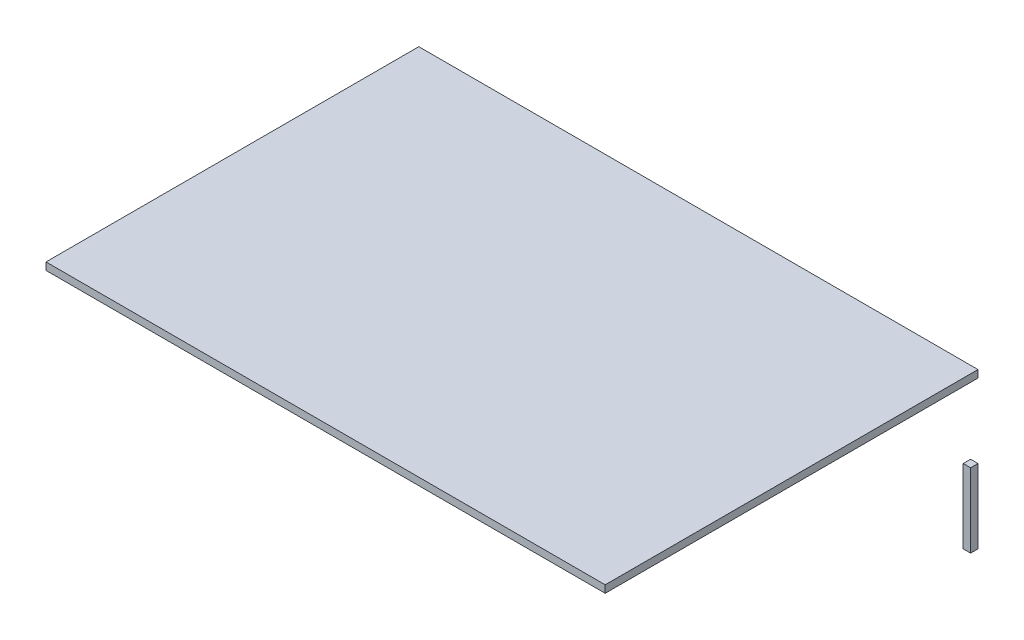
SolidWorks part; units mm, degrees
ref_plane "Front Plane" through (0, 0, 0) normal (0, 0, 1) x (1, 0, 0)
ref_plane "Top Plane" through (0, 0, 0) normal (0, 1, 0) x (1, 0, 0)
ref_plane "Right Plane" through (0, 0, 0) normal (1, 0, 0) x (0, 0, -1)
sketch "Sketch1" plane through (0, 0, 0) normal (0, 1, 0) x (1, 0, 0)
  line L1 (-37.5, -25) -> (37.5, -25)
  line L2 (-37.5, -25) -> (-37.5, 25)
  line L3 (-37.5, 25) -> (37.5, 25)
  line L4 (37.5, -25) -> (37.5, 25)
  line L5 (-37.5, -25) -> (37.5, 25) construction
  line L6 (-37.5, 25) -> (37.5, -25) construction
  point P0 (0, 0)
  dimension "D1" = 50
  dimension "D2" = 75
extrude "Boss-Extrude1" add sketch "Sketch1" along normal blind 10
sketch "Sketch2" plane through (0, 10, 0) normal (0, 1, 0) x (1, 0, 0)
  line L0 (37.5, 0) -> (37.5, 25) construction
  line L1 (37.5, -25) -> (37.5, 25) construction
  line L2 (37.5, 12.5) -> (-37.5, 12.5) construction
  line L3 (-37.5, 25) -> (-37.5, -25) construction
  line L4 (37.5, 19.5) -> (-37.5, 19.5) construction
  text T0 "TEST ONE " font "Century Gothic" height 7
  dimension "D1" = 7
extrude "Boss-Extrude2" add sketch "Sketch2" along normal blind 2
sketch "Sketch3" plane through (0, 10, 0) normal (0, 1, 0) x (1, 0, 0)
  line L0 (-37.5, 0) -> (-31.5, 0) construction
  line L1 (-37.5, 25) -> (-37.5, -25) construction
  line L2 (-31.5, -6) -> (-31.5, 6)
  line L3 (-31.5, 6) -> (-31.5, -6)
  line L4 (-31.5, -6) -> (-30.5, -6)
  line L5 (-30.5, -6) -> (-30.5, 6)
  line L6 (-30.5, 6) -> (-31.5, 6)
  line L7 (-37.5, -0.5) -> (-31.5, -0.5)
  line L8 (-37.5, 0.5) -> (-31.5, 0.5)
  line L9 (-30.5, 0) -> (-27.5, 0)
  line L10 (-29, 0) -> (-29, 1.3474)
  line L11 (-37.5, -0.5) -> (-31.5, -0.5)
  line L12 (-37.5, 0.5) -> (-31.5, 0.5)
  line L13 (-30.5, -6) -> (-31.5, -6)
  line L14 (-31.5, 6) -> (-30.5, 6)
  line L15 (-31.5, -6) -> (-30.5, -6)
  line L16 (-30.5, 6) -> (-31.5, 6)
  line L17 (-37.5, -0.5) -> (-31.5, -0.5)
  line L18 (-37.5, 0.5) -> (-31.5, 0.5)
  line L19 (-37.5, -0.5) -> (-31.5, -0.5)
  line L20 (-37.5, 0.5) -> (-31.5, 0.5)
  line L21 (-30.5, -6) -> (-31.5, -6)
  line L22 (-31.5, 6) -> (-30.5, 6)
  line L23 (-31.5, -6) -> (-30.5, -6)
  line L24 (-30.5, 6) -> (-31.5, 6)
  line L25 (-37.5, -0.5) -> (-31.5, -0.5)
  line L26 (-37.5, 0.5) -> (-31.5, 0.5)
  line L27 (-37.5, -0.5) -> (-31.5, -0.5)
  line L28 (-37.5, 0.5) -> (-31.5, 0.5)
  line L29 (-30.5, -6) -> (-31.5, -6)
  line L30 (-31.5, 6) -> (-30.5, 6)
  line L31 (-31.5, -6) -> (-30.5, -6)
  line L32 (-30.5, 6) -> (-31.5, 6)
  line L33 (-37.5, -0.5) -> (-31.5, -0.5)
  line L34 (-37.5, 0.5) -> (-31.5, 0.5)
  line L35 (-37.5, -0.5) -> (-31.5, -0.5)
  line L36 (-37.5, 0.5) -> (-31.5, 0.5)
  line L37 (-30.5, -6) -> (-31.5, -6)
  line L38 (-31.5, 6) -> (-30.5, 6)
  line L39 (-27.5, 0) -> (-27.5, 6)
  line L40 (-27.5, 6) -> (-26.5, 6)
  line L41 (-26.5, 6) -> (-26.5, -6)
  line L42 (-26.5, -6) -> (-27.5, -6)
  line L43 (-27.5, -6) -> (-27.5, 0)
  line L44 (-26.5, 0) -> (-20.5, 0)
  line L45 (-26.5, -0.5) -> (-20.5, -0.5)
  line L46 (-26.5, 0.5) -> (-20.5, 0.5)
  line L47 (-20.5, 0.5) -> (-20.5, -0.5)
  line L48 (-37.5, 0.5) -> (-37.5, -0.5)
  dimension "D1" = 6
  dimension "D2" = 6
  dimension "D3" = 6
  dimension "D4" = 1
  dimension "D7" = 3
  dimension "D5" = 6
  dimension "D6" = 1
  dimension "D8" = 0.5
  dimension "D9" = 0.5
extrude "Boss-Extrude3" add sketch "Sketch3" along normal blind 2 contours L5 L6 L2 L3 L4 | L48 L0 L2 L8 | L0 L48 L7 L3 | L43 L42 L41 L40 L39 | L47 L46 L41 L44 | L47 L44 L41 L45
sketch "Sketch4" plane through (0, 10, 0) normal (0, 1, 0) x (1, 0, 0)
  line L0 (-20.5, 0) -> (-17.5, 0)
  line L1 (-20.5, 0.5) -> (-20.5, -0.5) construction
  line L2 (-19, 0) -> (-19, 1.3773)
  line L3 (-26.5, -0.5) -> (-20.5, -0.5) construction
  line L4 (-20.5, -0.5) -> (-20.5, 0.5) construction
  line L5 (-20.5, 0.5) -> (-26.5, 0.5) construction
  line L6 (-26.5, 0.5) -> (-26.5, 6) construction
  line L7 (-26.5, 6) -> (-27.5, 6) construction
  line L8 (-27.5, 6) -> (-27.5, -6) construction
  line L9 (-27.5, -6) -> (-26.5, -6) construction
  line L10 (-26.5, -6) -> (-26.5, -0.5) construction
  line L11 (-30.5, -6) -> (-30.5, 6) construction
  line L12 (-30.5, 6) -> (-31.5, 6) construction
  line L13 (-31.5, 6) -> (-31.5, 0.5) construction
  line L14 (-31.5, 0.5) -> (-37.5, 0.5) construction
  line L15 (-37.5, 0.5) -> (-37.5, -0.5) construction
  line L16 (-37.5, -0.5) -> (-31.5, -0.5) construction
  line L17 (-31.5, -0.5) -> (-31.5, -6) construction
  line L18 (-31.5, -6) -> (-30.5, -6) construction
  line L19 (-26.5, -0.5) -> (-20.5, -0.5)
  line L20 (-20.5, -0.5) -> (-20.5, 0.5)
  line L21 (-20.5, 0.5) -> (-26.5, 0.5)
  line L22 (-26.5, 0.5) -> (-26.5, 6)
  line L23 (-26.5, 6) -> (-27.5, 6)
  line L24 (-27.5, 6) -> (-27.5, -6)
  line L25 (-27.5, -6) -> (-26.5, -6)
  line L26 (-26.5, -6) -> (-26.5, -0.5)
  line L27 (-30.5, -6) -> (-30.5, 6)
  line L28 (-30.5, 6) -> (-31.5, 6)
  line L29 (-31.5, 6) -> (-31.5, 0.5)
  line L30 (-31.5, 0.5) -> (-37.5, 0.5)
  line L31 (-37.5, 0.5) -> (-37.5, -0.5)
  line L32 (-37.5, -0.5) -> (-31.5, -0.5)
  line L33 (-31.5, -0.5) -> (-31.5, -6)
  line L34 (-31.5, -6) -> (-30.5, -6)
  line L35 (-6.5, -6) -> (-7.5, -6)
  line L36 (-6.5, -0.5) -> (-6.5, -6)
  line L37 (-0.5, -0.5) -> (-6.5, -0.5)
  line L38 (-0.5, 0.5) -> (-0.5, -0.5)
  line L39 (-6.5, 0.5) -> (-0.5, 0.5)
  line L40 (-6.5, 6) -> (-6.5, 0.5)
  line L41 (-7.5, 6) -> (-6.5, 6)
  line L42 (-7.5, -6) -> (-7.5, 6)
  line L43 (-11.5, -6) -> (-11.5, -0.5)
  line L44 (-10.5, -6) -> (-11.5, -6)
  line L45 (-10.5, 6) -> (-10.5, -6)
  line L46 (-11.5, 6) -> (-10.5, 6)
  line L47 (-11.5, 0.5) -> (-11.5, 6)
  line L48 (-17.5, 0.5) -> (-11.5, 0.5)
  line L49 (-17.5, -0.5) -> (-17.5, 0.5)
  line L50 (-11.5, -0.5) -> (-17.5, -0.5)
  line L51 (-10.5, 6) -> (-6.5, -6)
  line L52 (-7.5, -6) -> (-11.5, 6)
  dimension "D1" = 3
extrude "Boss-Extrude4" add sketch "Sketch4" along normal blind 2 contours L45 L52 L47 L48 L49 L50 L43 L44 | L52 L42 L51 L45 | L52 L45 L46 | L42 L51 L36 L37 L38 L39 L40 L41 | L51 L42 L35
sketch "Sketch5" plane through (0, 0, 25) normal (0, 0, 1) x (1, 0, 0)
  line L4 (-37.5, 0) -> (37.5, 0)
  line L5 (37.5, 0) -> (37.5, 10)
  line L6 (37.5, 10) -> (-37.5, 10)
  line L7 (-37.5, 10) -> (-37.5, 0)
  line L8 (-37.5, 0) -> (37.5, 0)
  line L9 (37.5, 0) -> (37.5, 10)
  line L10 (37.5, 10) -> (-37.5, 10)
  line L11 (-37.5, 10) -> (-37.5, 0)
  dimension "D1" = 0
sketch "Sketch6" plane through (0, 10, 0) normal (0, 1, 0) x (1, 0, 0)
  line L0 (37.7, 25.2) -> (-37.7, 25.2)
  line L1 (-37.7, 25.2) -> (-37.7, 0.3)
  line L2 (-37.7, 0.3) -> (-31.3, 0.3)
  line L3 (-31.3, 0.3) -> (-31.3, 5.8)
  line L4 (-31.3, 5.8) -> (-30.7, 5.8)
  line L5 (-30.7, 5.8) -> (-30.7, -5.8)
  line L6 (-30.7, -5.8) -> (-31.3, -5.8)
  line L7 (-31.3, -5.8) -> (-31.3, -0.3)
  line L8 (-31.3, -0.3) -> (-37.7, -0.3)
  line L9 (-37.7, -0.3) -> (-37.7, -25.2)
  line L10 (-37.7, -25.2) -> (37.7, -25.2)
  line L11 (37.7, -25.2) -> (37.7, 25.2)
  line L12 (-37.5, 25) -> (-37.5, 0.5)
  line L13 (-37.5, 0.5) -> (-31.5, 0.5)
  line L14 (-31.5, 0.5) -> (-31.5, 6)
  line L15 (-31.5, 6) -> (-30.5, 6)
  line L16 (-30.5, 6) -> (-30.5, -6)
  line L17 (-30.5, -6) -> (-31.5, -6)
  line L18 (-31.5, -6) -> (-31.5, -0.5)
  line L19 (-31.5, -0.5) -> (-37.5, -0.5)
  line L20 (-37.5, -0.5) -> (-37.5, -25)
  line L21 (-37.5, -25) -> (37.5, -25)
  line L22 (37.5, -25) -> (37.5, 25)
  line L23 (37.5, 25) -> (-37.5, 25)
  line L24 (-37.5, 25) -> (-37.5, 0.5)
  line L25 (-37.5, 0.5) -> (-31.5, 0.5)
  line L26 (-31.5, 0.5) -> (-31.5, 6)
  line L27 (-31.5, 6) -> (-30.5, 6)
  line L28 (-30.5, 6) -> (-30.5, -6)
  line L29 (-30.5, -6) -> (-31.5, -6)
  line L30 (-31.5, -6) -> (-31.5, -0.5)
  line L31 (-31.5, -0.5) -> (-37.5, -0.5)
  line L32 (-37.5, -0.5) -> (-37.5, -25)
  line L33 (-37.5, -25) -> (37.5, -25)
  line L34 (37.5, -25) -> (37.5, 25)
  line L35 (37.5, 25) -> (-37.5, 25)
  dimension "D1" = 0
  dimension "D2" = 0.2
extrude "Boss-Extrude6" add sketch "Sketch6" against normal through all
sketch "Sketch8" plane through (0, 10, 0) normal (0, 1, 0) x (1, 0, 0)
  line L16 (-37.5, -0.3) -> (-37.5, -25)
  line L17 (-37.5, -25) -> (37.5, -25)
  line L18 (37.5, -25) -> (37.5, 25)
  line L19 (37.5, 25) -> (-37.5, 25)
  line L20 (-37.5, 25) -> (-37.5, 0.3)
  line L21 (-37.7, 0.3) -> (-37.7, -0.3)
  line L22 (-37.5, -0.3) -> (-37.5, 0.3)
  line L32 (-37.5, 0.3) -> (-37.5, 0.5)
  line L33 (-37.5, 0.5) -> (-31.5, 0.5)
  line L34 (-31.5, 0.5) -> (-31.5, 6)
  line L35 (-31.5, 6) -> (-30.5, 6)
  line L36 (-30.5, 6) -> (-30.5, -6)
  line L37 (-30.5, -6) -> (-31.5, -6)
  line L38 (-31.5, -6) -> (-31.5, -0.5)
  line L39 (-31.5, -0.5) -> (-37.5, -0.5)
  line L40 (-37.5, -0.5) -> (-37.5, -0.3)
  line L41 (-37.5, -0.3) -> (-37.7, -0.3)
  line L42 (-37.7, -0.3) -> (-37.7, -25.2)
  line L43 (-37.7, -25.2) -> (37.7, -25.2)
  line L44 (37.7, -25.2) -> (37.7, 25.2)
  line L45 (37.7, 25.2) -> (-37.7, 25.2)
  line L46 (-37.7, 25.2) -> (-37.7, 0.3)
  line L47 (-37.7, 0.3) -> (-37.5, 0.3)
  line L48 (-37.5, 0.3) -> (-37.5, 0.5)
  line L49 (-37.5, 0.5) -> (-31.5, 0.5)
  line L50 (-31.5, 0.5) -> (-31.5, 6)
  line L51 (-31.5, 6) -> (-30.5, 6)
  line L52 (-30.5, 6) -> (-30.5, -6)
  line L53 (-30.5, -6) -> (-31.5, -6)
  line L54 (-31.5, -6) -> (-31.5, -0.5)
  line L55 (-31.5, -0.5) -> (-37.5, -0.5)
  line L56 (-37.5, -0.5) -> (-37.5, -0.3)
  line L57 (-37.5, -0.3) -> (-37.7, -0.3)
  line L58 (-37.7, -0.3) -> (-37.7, -25.2)
  line L59 (-37.7, -25.2) -> (37.7, -25.2)
  line L60 (37.7, -25.2) -> (37.7, 25.2)
  line L61 (37.7, 25.2) -> (-37.7, 25.2)
  line L62 (-37.7, 25.2) -> (-37.7, 0.3)
  line L63 (-37.7, 0.3) -> (-37.5, 0.3)
  dimension "D1" = 0
  dimension "D2" = 0.2
extrude "Cut-Extrude2" cut sketch "Sketch8" against normal through all contours L54 L55 L16 L17 L18 L19 L20 L49 L50 L51 L52 L53
sketch "Sketch9" plane through (-37.7, 0, 0) normal (-1, 0, 0) x (0, 0, 1)
  line L1 (-0.3, 10) -> (0.3, 10)
  line L2 (-0.3, 10) -> (-0.3, 0)
  line L3 (-0.3, 0) -> (0.3, 0)
  line L4 (25.2, 10) -> (0.3, 10)
  line L5 (0.3, 10) -> (0.3, 0)
  line L6 (0.3, 0) -> (25.2, 0)
  line L7 (25.2, 0) -> (25.2, 10)
  line L8 (25.2, 10) -> (0.3, 10)
  line L9 (0.3, 10) -> (0.3, 0)
  line L10 (0.3, 0) -> (25.2, 0)
  line L11 (25.2, 0) -> (25.2, 10)
  line L12 (-0.3, 10) -> (-25.2, 10)
  line L13 (-25.2, 10) -> (-25.2, 0)
  line L14 (-25.2, 0) -> (-0.3, 0)
  line L15 (-0.3, 0) -> (-0.3, 10)
  line L16 (-0.3, 10) -> (-25.2, 10)
  line L17 (-25.2, 10) -> (-25.2, 0)
  line L18 (-25.2, 0) -> (-0.3, 0)
  line L19 (-0.3, 0) -> (-0.3, 10)
  line L20 (0.3, 10) -> (0.3, 0)
  line M9 (25.2, 10) -> (0.3, 10)
  line M10 (0.3, 10) -> (0.3, 0)
  line M11 (0.3, 0) -> (25.2, 0)
  line M12 (25.2, 0) -> (25.2, 10)
  dimension "D1" = 0
  dimension "D2" = 0
extrude "Boss-Extrude8" add sketch "Sketch9" along normal blind 0.2 contours L17 L18 L2 L16 | L2 L3 L1 M10 | M12 M9 M10 M11
sketch "Sketch10" plane through (0, 10, 0) normal (0, 1, 0) x (1, 0, 0)
  line L0 (-37.7, 0.3) -> (-37.7, 25)
  line L1 (-37.5, 25) -> (-37.7, 25)
  line L2 (-37.5, 25) -> (-37.5, -25)
  line L3 (-37.5, -25) -> (-37.7, -25)
  line L4 (-37.7, 0.3) -> (-37.7, -25)
extrude "Cut-Extrude3" cut sketch "Sketch10" against normal through all
ref_plane "Plane1" through (0, 20, 0) normal (0, 1, 0) x (1, 0, 0)
sketch "Sketch11" plane through (0, 20, 0) normal (0, 1, 0) x (1, 0, 0)
  line L1 (-37.9, 25.2) -> (37.5, 25.2)
  line L2 (-37.9, 25.2) -> (-37.9, -25)
  line L3 (-37.9, -25) -> (37.5, -25)
  line L4 (37.5, 25.2) -> (37.5, -25)
extrude "Boss-Extrude9" add sketch "Sketch11" along normal blind 1 separate body
sketch "Sketch12" plane through (0, 21, 0) normal (0, 1, 0) x (1, 0, 0)
  line L2 (-37.9, 25.2) -> (37.7, 25.2)
  line L3 (-37.9, 25.2) -> (-37.9, -25.2)
  line L4 (-37.9, -25.2) -> (37.7, -25.2)
  line L5 (37.7, 25.2) -> (37.7, -25.2)
extrude "Boss-Extrude10" add sketch "Sketch12" against normal blind 1
sketch "Sketch13" plane through (0, 10, 0) normal (0, 1, 0) x (1, 0, 0)
  line L1 (37.7, 25.2) -> (36.7, 25.2)
  line L2 (37.7, 25.2) -> (37.7, 24.2)
  line L3 (37.7, 24.2) -> (36.7, 24.2)
  line L4 (36.7, 25.2) -> (36.7, 24.2)
  dimension "D1" = 1
  dimension "D2" = 1
extrude "Boss-Extrude11" add sketch "Sketch13" against normal through all
sketch "Sketch14" plane through (0, 10, 0) normal (0, 1, 0) x (1, 0, 0)
  line L0 (36.7, 24.2) -> (36.7, 25.2)
  line L1 (36.7, 24.2) -> (37.7, 24.2)
  line L4 (37.7, -25.2) -> (37.7, 25.2)
  line L5 (37.7, 25.2) -> (-37.9, 25.2)
  line L6 (-37.9, 25.2) -> (-37.9, -25.2)
  line L7 (-37.9, -25.2) -> (37.7, -25.2)
  line L8 (37.7, -25.2) -> (37.7, 25.2)
  line L9 (37.7, 25.2) -> (-37.9, 25.2)
  line L10 (-37.9, 25.2) -> (-37.9, -25.2)
  line L11 (-37.9, -25.2) -> (37.7, -25.2)
  line M5 (36.7, 24.2) -> (37.5, 24.2)
  line M6 (37.5, 24.2) -> (37.5, -25)
  line M7 (37.5, -25) -> (-37.7, -25)
  line M8 (-37.7, -25) -> (-37.7, 25)
  line M9 (-37.7, 25) -> (36.7, 25)
  line M10 (36.7, 25) -> (36.7, 24.2)
  line M11 (37.7, -25.2) -> (37.7, 25.2)
  line M12 (37.7, 25.2) -> (-37.9, 25.2)
  line M13 (-37.9, 25.2) -> (-37.9, -25.2)
  line M14 (-37.9, -25.2) -> (37.7, -25.2)
  dimension "D1" = 0
extrude "Cut-Extrude4" cut sketch "Sketch14" against normal through all contours M5 M10 M9 M8 M7 M6 | L1 L0 M6 M7 M8 M9 M12 M13 M14 M11
